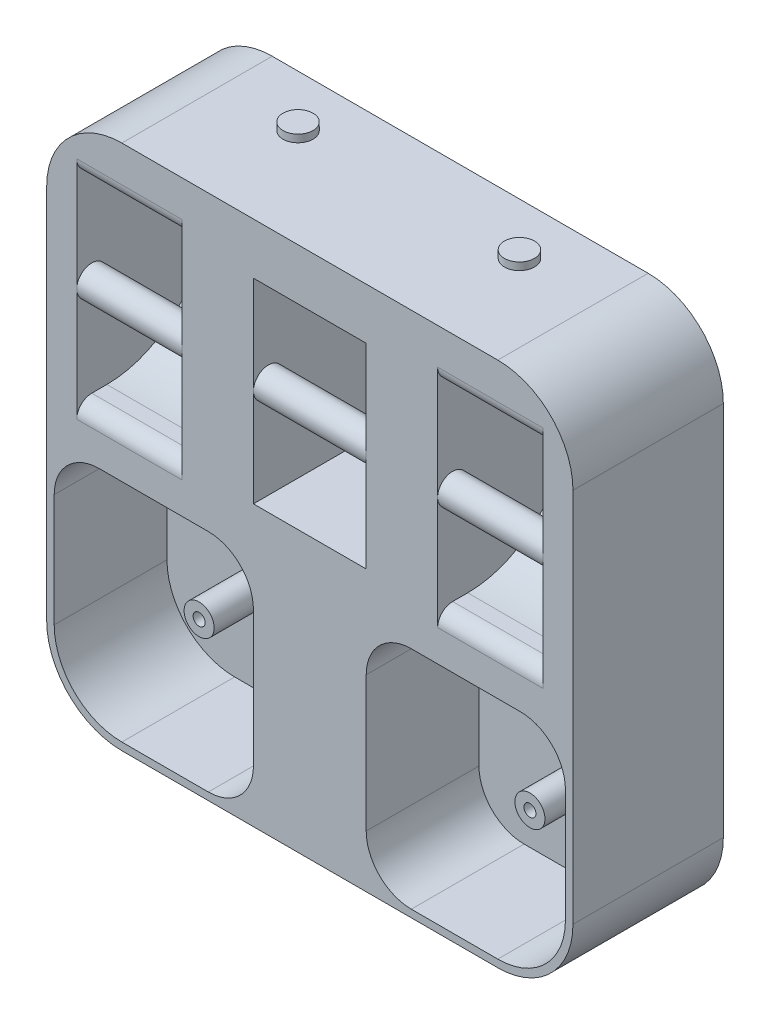
SolidWorks part; units mm, degrees
ref_plane "前视基准面" through (0, 0, 0) normal (0, 0, 1) x (1, 0, 0)
ref_plane "上视基准面" through (0, 0, 0) normal (0, 1, 0) x (1, 0, 0)
ref_plane "右视基准面" through (0, 0, 0) normal (1, 0, 0) x (0, 0, -1)
sketch "草图1" plane through (0, 0, 0) normal (0, 0, 1) x (1, 0, 0)
  line L1 (175, -175) -> (-175, -175)
  line L2 (175, -175) -> (175, 175)
  line L3 (175, 175) -> (-175, 175)
  line L4 (-175, -175) -> (-175, 175)
  line L5 (175, -175) -> (-175, 175) construction
  line L6 (175, 175) -> (-175, -175) construction
  point P0 (0, 0)
  dimension "D1" = 350
  dimension "D2" = 350
extrude "凸台-拉伸1" add sketch "草图1" along normal blind 100
fillet "圆角1" radius 50 4 edges at (175, -175, 50) (175, 175, 50) (-175, -175, 50) (-175, 175, 50)
sketch "草图2" plane through (0, 0, 100) normal (0, 0, 1) x (1, 0, 0)
  line L0 (0, 175) -> (0, -175) construction
  line L1 (125, 175) -> (-125, 175) construction
  line L2 (-125, -175) -> (125, -175) construction
  line L3 (-120, 175) -> (-120, 75) construction
  line L4 (-120, 75) -> (-175, 75) construction
  line L5 (-175, 125) -> (-175, -125) construction
  dimension "D1" = 55
  dimension "D2" = 100
ref_plane "基准面1" through (-120, 0, 0) normal (-1, 0, 0) x (0, 0, 1)
sketch "草图3" plane through (-120, 0, 0) normal (-1, 0, 0) x (0, 0, 1)
  line L0 (100, 75.935) -> (0, 75.935) construction
  line L1 (100, 175) -> (100, -175) construction
  line L2 (0, 125) -> (0, -125) construction
  line L3 (80, 10.935) -> (100, 10.935)
  line L4 (80, 140.935) -> (100, 140.935)
  line L5 (100, 140.935) -> (100, 10.935)
  line L6 (100, 10.935) -> (100, 140.935)
  arc A0 (80, 140.935) -> (80, 10.935) centre (80, 75.935) ccw
  dimension "D1" = 20
extrude "切除-拉伸1" cut sketch "草图3" against normal blind 35 and the other way blind 35 contours L0 L5 L4 A0 | L6 L0 A0 L3
mirror "镜向1" about plane through (0, 0, 0) normal (1, 0, 0) of "切除-拉伸1"
sketch "草图4" plane through (0, 0, 100) normal (0, 0, 1) x (1, 0, 0)
  line L0 (-85, 75.935) -> (85, 75.935) construction
  line L1 (-85, 140.935) -> (-85, 10.935) construction
  line L2 (85, 10.935) -> (85, 140.935) construction
  line L4 (37.5, 10.935) -> (-37.5, 10.935)
  line L5 (37.5, 10.935) -> (37.5, 140.935)
  line L6 (37.5, 140.935) -> (-37.5, 140.935)
  line L7 (-37.5, 10.935) -> (-37.5, 140.935)
  line L8 (37.5, 10.935) -> (-37.5, 140.935) construction
  line L9 (37.5, 140.935) -> (-37.5, 10.935) construction
  point P6 (0, 75.935)
  dimension "D1" = 75
extrude "切除-拉伸2" cut sketch "草图4" against normal blind 75
sketch "草图5" plane through (-155, 0, 0) normal (1, 0, 0) x (0, 0, -1)
  line L0 (-15, 75.935) -> (-100, 75.935) construction
  line L1 (-100, 140.935) -> (-100, 10.935) construction
  arc A0 (-80, 10.935) -> (-80, 140.935) centre (-80, 75.935) ccw construction
  circle A1 centre (-90, 75.935) radius 10
  dimension "D1" = 10
extrude "凸台-拉伸3" add sketch "草图5" along normal up to surface (310 mm away) up to face at (155, 75.935, 73.75)
fillet "圆角2" radius 10 4 edges at (120, 140.935, 100) (120, 10.935, 100) (-120, 10.935, 100) (-120, 140.935, 100)
sketch "草图6" plane through (0, 0, 100) normal (0, 0, 1) x (1, 0, 0)
  line L0 (0, 175) -> (0, -175) construction
  line L1 (125, 175) -> (-125, 175) construction
  line L2 (-125, -175) -> (125, -175) construction
  line L3 (-125, -170) -> (125, -170)
  line L4 (170, -125) -> (170, 125)
  line L5 (125, 170) -> (-125, 170)
  line L6 (-170, 125) -> (-170, -125)
  line L7 (170, -20) -> (-170, -20)
  arc A0 (125, -170) -> (170, -125) centre (125, -125) ccw
  arc A1 (170, 125) -> (125, 170) centre (125, 125) ccw
  arc A2 (-125, 170) -> (-170, 125) centre (-125, 125) ccw
  arc A3 (-170, -125) -> (-125, -170) centre (-125, -125) ccw
  dimension "D1" = 150
extrude "切除-拉伸3" cut sketch "草图6" against normal blind 75 contours L7 L0 L3 A0 L4 | L0 L7 L6 A3 L3
sketch "草图7" plane through (0, 0, 25) normal (0, 0, 1) x (1, 0, 0)
  line L0 (0, 0) -> (0, -175) construction
  line L1 (-125, -175) -> (125, -175) construction
  line L2 (-110, -110) -> (110, -110) construction
  line L4 (-125, -170) -> (125, -170) construction
  line L5 (170, -125) -> (170, -20) construction
  circle A0 centre (110, -110) radius 4
  circle A1 centre (110, -110) radius 10
  circle A2 centre (-110, -110) radius 10
  circle A3 centre (-110, -110) radius 4
  point P10 (0, -110)
  dimension "D1" = 60
  dimension "D2" = 60
extrude "凸台-拉伸4" add sketch "草图7" along normal blind 38.62
sketch "草图8" plane through (0, 0, 25) normal (0, 0, 1) x (1, 0, 0)
  line L0 (37.5, 10.935) -> (37.5, -170) construction
  line L1 (-125, -170) -> (125, -170) construction
  line L2 (-37.5, 10.935) -> (-37.5, -170) construction
  line L3 (170, -20) -> (-170, -20) construction
  line L4 (37.5, -20) -> (-37.5, -20)
  line L5 (37.5, -20) -> (37.5, -170)
  line L6 (37.5, -170) -> (-37.5, -170)
  line L7 (-37.5, -20) -> (-37.5, -170)
extrude "凸台-拉伸5" add sketch "草图8" along normal up to surface (75 mm away) up to face at (0, -108.1066, 100)
fillet "圆角3" radius 30 6 edges at (37.5, -170, 62.5) (-37.5, -170, 62.5) (-170, -20, 62.5) (-37.5, -20, 62.5) (37.5, -20, 62.5) (170, -20, 62.5)
sketch "草图9" plane through (0, 175, 0) normal (0, 1, 0) x (1, 0, 0)
  line L0 (0, 0) -> (0, -100) construction
  line L1 (125, -100) -> (-125, -100) construction
  circle A0 centre (-73.6261, -34.223) radius 10
  circle A1 centre (73.6261, -34.223) radius 10
extrude "凸台-拉伸6" add sketch "草图9" along normal blind 5
